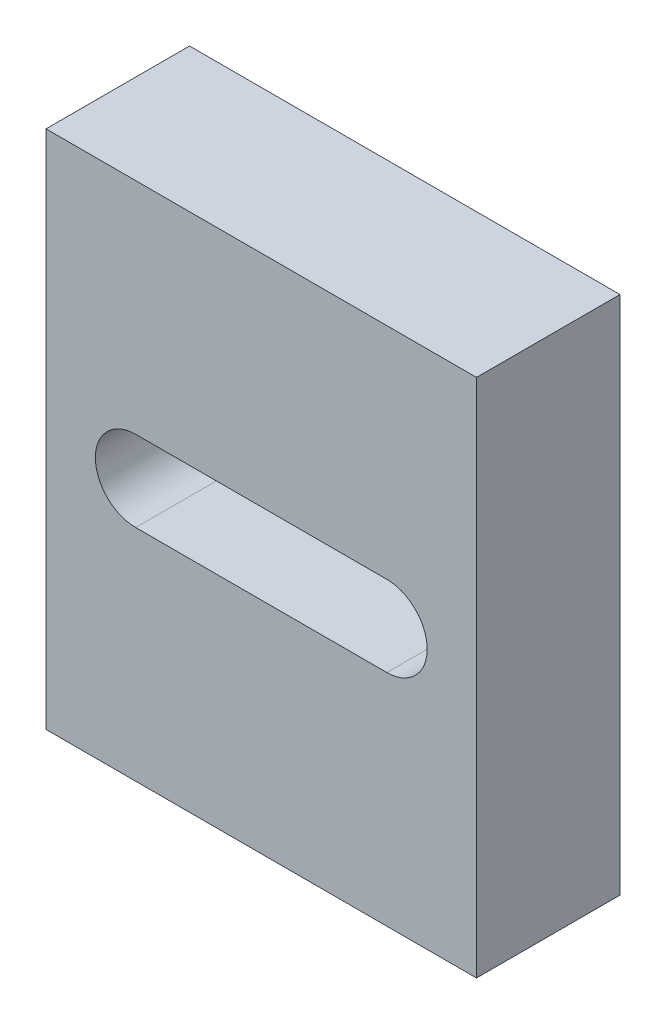
SolidWorks part; units mm, degrees
ref_plane "前视基准面" through (0, 0, 0) normal (0, 0, 1) x (1, 0, 0)
ref_plane "上视基准面" through (0, 0, 0) normal (0, 1, 0) x (1, 0, 0)
ref_plane "右视基准面" through (0, 0, 0) normal (1, 0, 0) x (0, 0, -1)
other "Configuration Table"
sketch "草图1" plane through (0, 0, 0) normal (0, 0, 1) x (1, 0, 0)
  line L1 (-24, -29) -> (24, -29)
  line L2 (-24, -29) -> (-24, 29)
  line L3 (-24, 29) -> (24, 29)
  line L4 (24, -29) -> (24, 29)
extrude "凸台-拉伸1" add sketch "草图1" against normal blind 16
sketch "草图2" plane through (0, 0, 0) normal (0, 0, 1) x (1, 0, 0)
  line L0 (-14, 0) -> (14, 0) construction
  line L1 (-14, 4.5) -> (14, 4.5)
  line L2 (-14, -4.5) -> (14, -4.5)
  arc A0 (-14, 4.5) -> (-14, -4.5) centre (-14, 0) ccw
  arc A1 (14, -4.5) -> (14, 4.5) centre (14, 0) ccw
  point P3 (0, 0)
  point P8 (0, 0)
extrude "切除-拉伸1" cut sketch "草图2" against normal through all
